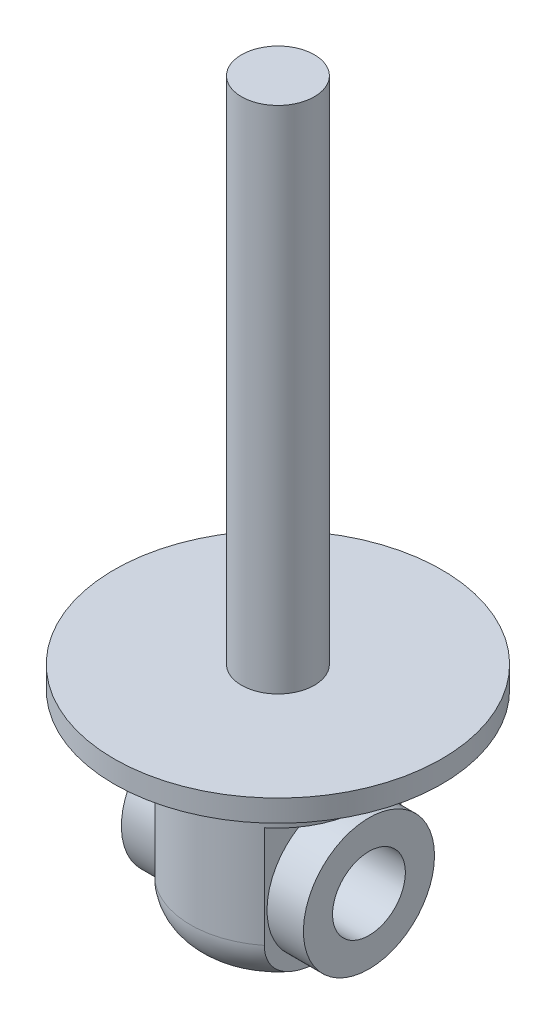
SolidWorks part; units mm, degrees
ref_plane "Front Plane" through (0, 0, 0) normal (0, 0, 1) x (1, 0, 0)
ref_plane "Top Plane" through (0, 0, 0) normal (0, 1, 0) x (1, 0, 0)
ref_plane "Right Plane" through (0, 0, 0) normal (1, 0, 0) x (0, 0, -1)
sketch "Sketch1" plane through (0, 0, 0) normal (0, 1, 0) x (1, 0, 0)
  circle A0 centre (0, 0) radius 22.5
  dimension "D1" = 45
extrude "Boss-Extrude1" add sketch "Sketch1" along normal blind 3
sketch "Sketch2" plane through (0, 3, 0) normal (0, 1, 0) x (1, 0, 0)
  circle A0 centre (0, 0) radius 5
  dimension "D1" = 10
extrude "Boss-Extrude2" add sketch "Sketch2" along normal blind 70
sketch "Sketch3" plane through (0, 0, 0) normal (0, -1, 0) x (1, 0, 0)
  circle A0 centre (0, 0) radius 12
  dimension "D1" = 24
extrude "Boss-Extrude3" add sketch "Sketch3" along normal blind 28
fillet "Fillet1" radius 6 1 edges at (0, -28, -12)
sketch "Sketch4" plane through (0, 0, 0) normal (0, 0, 1) x (1, 0, 0)
  line L0 (0, 0) -> (0, -28) construction
  line L1 (-6, -28) -> (6, -28) construction
  line L2 (7.5, -28) -> (27.07, -28)
  line L3 (27.07, -28) -> (27.07, -8)
  line L4 (27.07, -8) -> (7.5, -8)
  line L5 (7.5, -8) -> (7.5, -28)
  line L6 (-7.5, -8) -> (-7.5, -28)
  line L7 (-27.07, -8) -> (-7.5, -8)
  line L8 (-27.07, -28) -> (-27.07, -8)
  line L9 (-7.5, -28) -> (-27.07, -28)
  dimension "D1" = 15
  dimension "D2" = 20
  dimension "D3" = 19.57
extrude "Cut-Extrude1" cut sketch "Sketch4" against normal through all both and the other way through all
sketch "Sketch6" plane through (7.5, 0, 0) normal (1, 0, 0) x (0, 0, -1)
  line L0 (0, 0) -> (0, -27.8095) construction
  line L1 (-6, -28) -> (6, -28) construction
  circle A0 centre (0, -18) radius 5
  spline S0 degree 3 poles (-9.3675, -22) (-9.3675, -22.256) (-9.346, -22.5161) (-9.2617, -23.0236) (-9.1993, -23.2718) (-9.0353, -23.7573) (-8.9325, -23.9966) (-8.6933, -24.4529) (-8.5573, -24.67) (-8.2544, -25.0836) (-8.0864, -25.2813) (-7.7261, -25.6506) (-7.5349, -25.8216) (-6.9312, -26.2977) (-6.4844, -26.5672) (-5.5607, -27.0045) (-5.0803, -27.1758) (-4.0917, -27.4469) (-3.5846, -27.5457) (-2.5722, -27.6899) (-2.0636, -27.7363) (-1.0432, -27.7958) (-0.5315, -27.8091) (0.4943, -27.8098) (1.0101, -27.797) (2.0342, -27.7387) (2.5445, -27.6929) (3.56, -27.5501) (4.0672, -27.4524) (5.0646, -27.1812) (5.5488, -27.0094) (6.4792, -26.5703) (6.9277, -26.3001) (7.5323, -25.8239) (7.7237, -25.6529) (8.0841, -25.2839) (8.2538, -25.0844) (8.7096, -24.462) (8.9491, -24.0109) (9.1993, -23.2725) (9.2623, -23.0206) (9.3462, -22.5143) (9.3675, -22.2585) (9.3675, -22) knots 0 0 0 0 0.03125 0.03125 0.0625 0.0625 0.09375 0.09375 0.125 0.125 0.15625 0.15625 0.1875 0.1875 0.25 0.25 0.3125 0.3125 0.375 0.375 0.4375 0.4375 0.5 0.5 0.5625 0.5625 0.625 0.625 0.6875 0.6875 0.75 0.75 0.8125 0.8125 0.84375 0.84375 0.875 0.875 0.9375 0.9375 0.96875 0.96875 1 1 1 1 construction
  dimension "D1" = 10
  dimension "D2" = 10
extrude "Cut-Extrude2" cut sketch "Sketch6" against normal through all and the other way through all
sketch "Sketch8" plane through (0, 0, 0) normal (1, 0, 0) x (0, 0, -1)
  circle A0 centre (0, -18) radius 9
  circle A1 centre (0, -18) radius 5 construction
  circle A2 centre (0, -18) radius 5
  dimension "D1" = 18
extrude "Boss-Extrude4" add sketch "Sketch8" along normal mid plane 25
